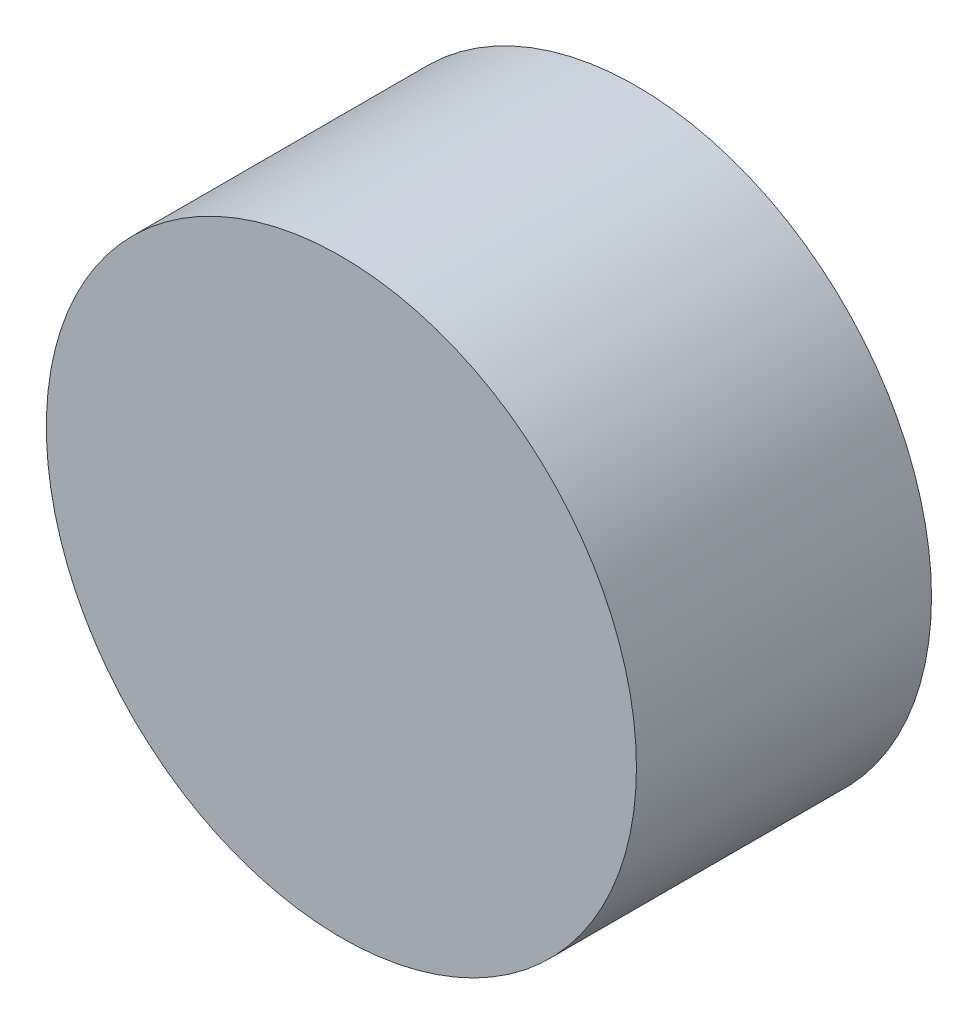
SolidWorks part; units mm, degrees
ref_plane "前视基准面" through (0, 0, 0) normal (0, 0, 1) x (1, 0, 0)
ref_plane "上视基准面" through (0, 0, 0) normal (0, 1, 0) x (1, 0, 0)
ref_plane "右视基准面" through (0, 0, 0) normal (1, 0, 0) x (0, 0, -1)
sketch "草图1" plane through (0, 0, 0) normal (0, 0, 1) x (1, 0, 0)
  circle A0 centre (-8.4121, 9.4135) radius 4
extrude "凸台-拉伸1" add sketch "草图1" along normal blind 4
